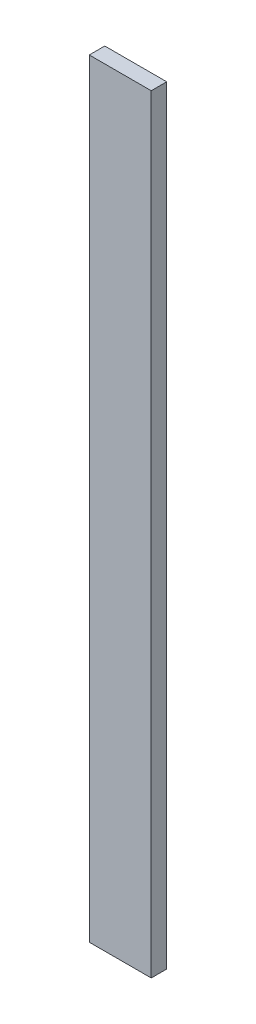
SolidWorks part; units mm, degrees
material "Spruce"
ref_plane "Front Plane" through (0, 0, 0) normal (0, 0, 1) x (1, 0, 0)
ref_plane "Top Plane" through (0, 0, 0) normal (0, 1, 0) x (1, 0, 0)
ref_plane "Right Plane" through (0, 0, 0) normal (1, 0, 0) x (0, 0, -1)
sketch "Sketch1" plane through (0, 0, 0) normal (0, 0, 1) x (1, 0, 0)
  line L0 (-0.4127, 217.032) -> (5.9373, 217.032)
  line L1 (5.9373, 217.032) -> (5.9373, 295.7732)
  line L2 (5.9373, 295.7732) -> (-0.4127, 295.7732)
  line L3 (-0.4127, 295.7732) -> (-0.4127, 217.032)
extrude "Boss-Extrude1" add sketch "Sketch1" along normal blind 1.5875
